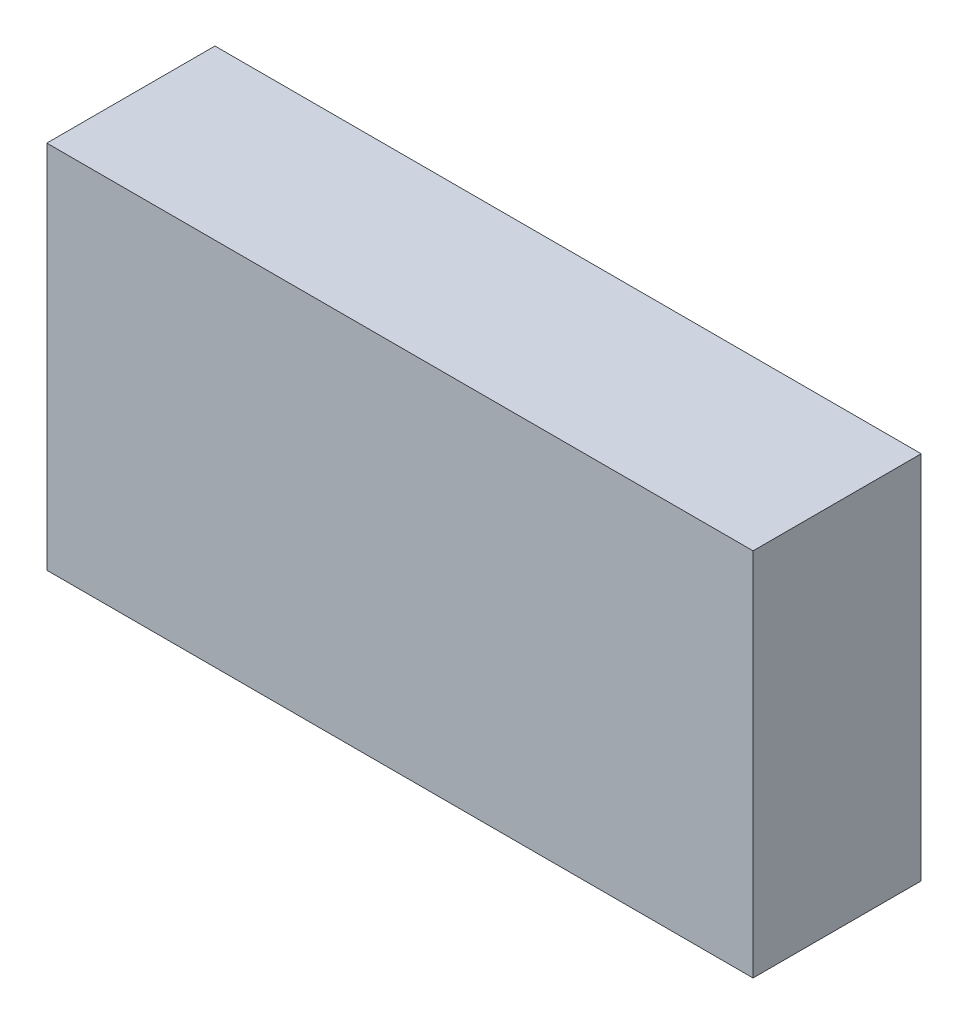
SolidWorks part; units mm, degrees
ref_plane "Front Plane" through (0, 0, 0) normal (0, 0, 1) x (1, 0, 0)
ref_plane "Top Plane" through (0, 0, 0) normal (0, 1, 0) x (1, 0, 0)
ref_plane "Right Plane" through (0, 0, 0) normal (1, 0, 0) x (0, 0, -1)
sketch "Sketch2" plane through (0, 0, 0) normal (1, 0, 0) x (0, 0, -1)
  line L1 (-5, 11) -> (5, 11)
  line L2 (-5, 11) -> (-5, -11)
  line L3 (-5, -11) -> (5, -11)
  line L4 (5, 11) -> (5, -11)
  line L5 (-5, 11) -> (5, -11) construction
  line L6 (-5, -11) -> (5, 11) construction
  point P0 (0, 0)
  dimension "D1" = 10
  dimension "D2" = 22
extrude "Boss-Extrude1" add sketch "Sketch2" along normal mid plane 42
sketch "Sketch3" plane through (0, -11, 0) normal (0, -1, 0) x (1, 0, 0)
  line L0 (-21, 5) -> (-21, -5) construction
  circle A0 centre (-16, 0) radius 2
  circle A1 centre (-5, 0) radius 2
  point P6 (0, 0)
  dimension "D2" = 5
  dimension "D3" = 4
  dimension "D4" = 4
  dimension "D1" = 11
extrude "Cut-Extrude1" cut sketch "Sketch3" against normal blind 5
